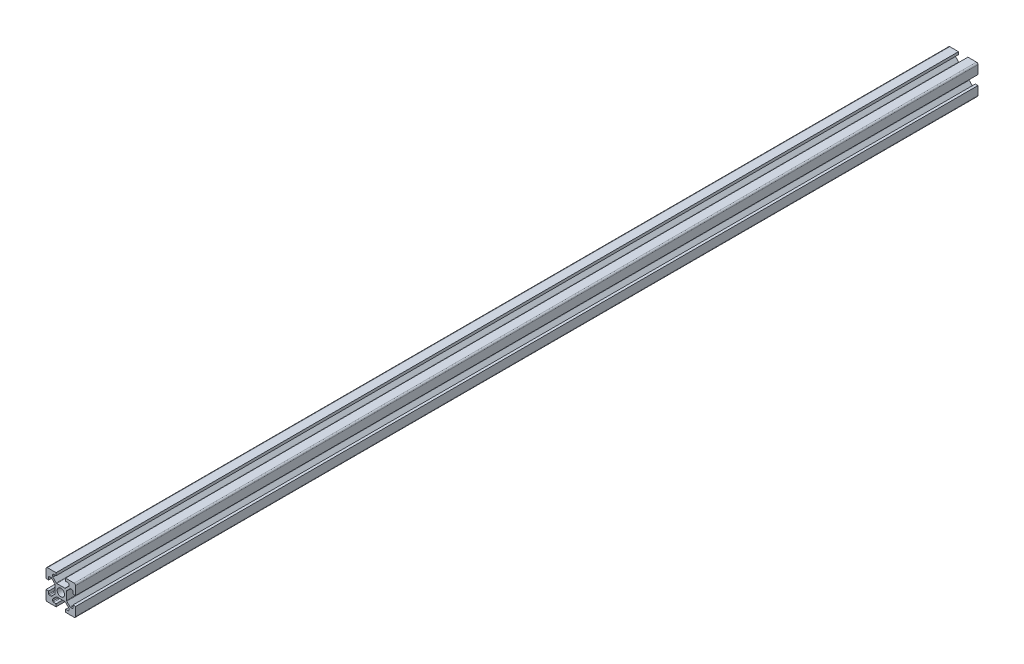
SolidWorks part; units mm, degrees
material "1060 Alloy"
ref_plane "Front Plane" through (0, 0, 0) normal (0, 0, 1) x (1, 0, 0)
ref_plane "Top Plane" through (0, 0, 0) normal (0, 1, 0) x (1, 0, 0)
ref_plane "Right Plane" through (0, 0, 0) normal (1, 0, 0) x (0, 0, -1)
sketch "Sketch1" plane through (0, 0, 0) normal (0, 0, 1) x (1, 0, 0)
  line L0 (20, 0) -> (-8.059, 28.059) construction
  line L1 (0, 0) -> (6.8, 0)
  line L2 (0, 0) -> (0, 6.8)
  line L3 (0, 20) -> (6.8, 20)
  line L4 (20, 0) -> (20, 6.8)
  line L5 (6.8, 20) -> (6.8, 18.2)
  line L6 (20, 20) -> (8.2322, 8.2322) construction
  line L7 (12.95, 6.1) -> (7.05, 6.1)
  line L8 (13.9, 7.05) -> (13.9, 12.95)
  line L9 (12.95, 13.9) -> (7.05, 13.9)
  line L10 (6.1, 7.05) -> (6.1, 12.95)
  line L11 (13.9, 6.1) -> (6.1, 13.9) construction
  line L12 (13.9, 13.9) -> (6.1, 6.1) construction
  line L13 (4.55, 16.4) -> (7.05, 13.9)
  line L14 (13.2, 18.2) -> (13.2, 20)
  line L15 (1.8, 6.8) -> (0, 6.8)
  line L16 (0, 13.2) -> (0, 20)
  line L17 (0, 13.2) -> (1.8, 13.2)
  line L18 (10, 10) -> (10, 13.9) construction
  line L19 (16.4, 4.55) -> (13.9, 7.05)
  line L20 (4.55, 16.4) -> (4.55, 18.2)
  line L21 (4.55, 18.2) -> (6.8, 18.2)
  line L22 (13.2, 18.2) -> (15.45, 18.2)
  line L23 (15.45, 18.2) -> (15.45, 16.4)
  line L24 (15.45, 16.4) -> (12.95, 13.9)
  line L25 (16.4, 4.55) -> (18.2, 4.55)
  line L26 (18.2, 4.55) -> (18.2, 6.8)
  line L27 (20, 6.8) -> (18.2, 6.8)
  line L28 (18.2, 13.2) -> (20, 13.2)
  line L29 (18.2, 13.2) -> (18.2, 15.45)
  line L30 (18.2, 15.45) -> (16.4, 15.45)
  line L31 (16.4, 15.45) -> (13.9, 12.95)
  line L32 (1.8, 4.55) -> (3.6, 4.55)
  line L33 (3.6, 15.45) -> (6.1, 12.95)
  line L34 (3.6, 15.45) -> (1.8, 15.45)
  line L35 (1.8, 15.45) -> (1.8, 13.2)
  line L36 (0, 13.2) -> (1.8, 13.2)
  line L37 (1.8, 6.8) -> (0, 6.8)
  line L38 (3.6, 4.55) -> (6.1, 7.05)
  line L39 (1.8, 6.8) -> (1.8, 4.55)
  line L40 (15.45, 3.6) -> (12.95, 6.1)
  line L41 (4.55, 3.6) -> (7.05, 6.1)
  line L42 (4.55, 1.8) -> (4.55, 3.6)
  line L43 (6.8, 1.8) -> (4.55, 1.8)
  line L44 (6.8, 1.8) -> (6.8, 0)
  line L45 (15.45, 3.6) -> (15.45, 1.8)
  line L46 (15.45, 1.8) -> (13.2, 1.8)
  line L47 (13.2, 0) -> (13.2, 1.8)
  line L48 (13.2, 20) -> (20, 20)
  line L49 (20, 13.2) -> (20, 20)
  line L50 (13.2, 0) -> (20, 0)
  line L51 (6.1, 6.1) -> (-5.5045, -5.5045) construction
  circle A0 centre (10, 10) radius 2.5
  point P25 (10, 16.4)
  point P39 (13.2, 19.1)
  point P46 (0.9, 6.8)
  dimension "D3" = 5
  dimension "D2" = 20
  dimension "D4" = 7.8
  dimension "D5" = 7.8
  dimension "D6" = 6.8
  dimension "D7" = 6.8
  dimension "D8" = 1.8
  dimension "D9" = 10.9
  dimension "D10" = 1.8
  dimension "D11" = 10.9
  dimension "D12" = 20
extrude "Boss-Extrude1" add sketch "Sketch1" along normal blind 609.6 contours L47 L50 L4 L27 L26 L25 L19 L8 L31 L30 L29 L28 L49 L48 L14 L22 L23 L24 L9 L13 L20 L21 L5 L3 L16 L17 L35 L34 L33 L10 L38 L32 L39 L15 L2 L1 L44 L43 L42 L41 L7 L40 L45 L46 A0
fillet "Fillet1" radius 1 4 edges at (20, 20, 304.8) (20, 0, 304.8) (0, 0, 304.8) (0, 20, 304.8)
fillet "Fillet2" radius 0.5 6 edges at (4.55, 18.2, 304.8) (4.55, 16.4, 304.8) (7.05, 13.9, 304.8) (15.45, 18.2, 304.8) (15.45, 16.4, 304.8) (12.95, 13.9, 304.8)
fillet "Fillet3" radius 0.5 6 edges at (18.2, 15.45, 304.8) (16.4, 15.45, 304.8) (13.9, 12.95, 304.8) (18.2, 4.55, 304.8) (13.9, 7.05, 304.8) (16.4, 4.55, 304.8)
fillet "Fillet4" radius 0.5 6 edges at (1.8, 15.45, 304.8) (3.6, 15.45, 304.8) (6.1, 12.95, 304.8) (3.6, 4.55, 304.8) (1.8, 4.55, 304.8) (6.1, 7.05, 304.8)
fillet "Fillet5" radius 0.5 6 edges at (7.05, 6.1, 304.8) (4.55, 3.6, 304.8) (4.55, 1.8, 304.8) (15.45, 1.8, 304.8) (15.45, 3.6, 304.8) (12.95, 6.1, 304.8)
